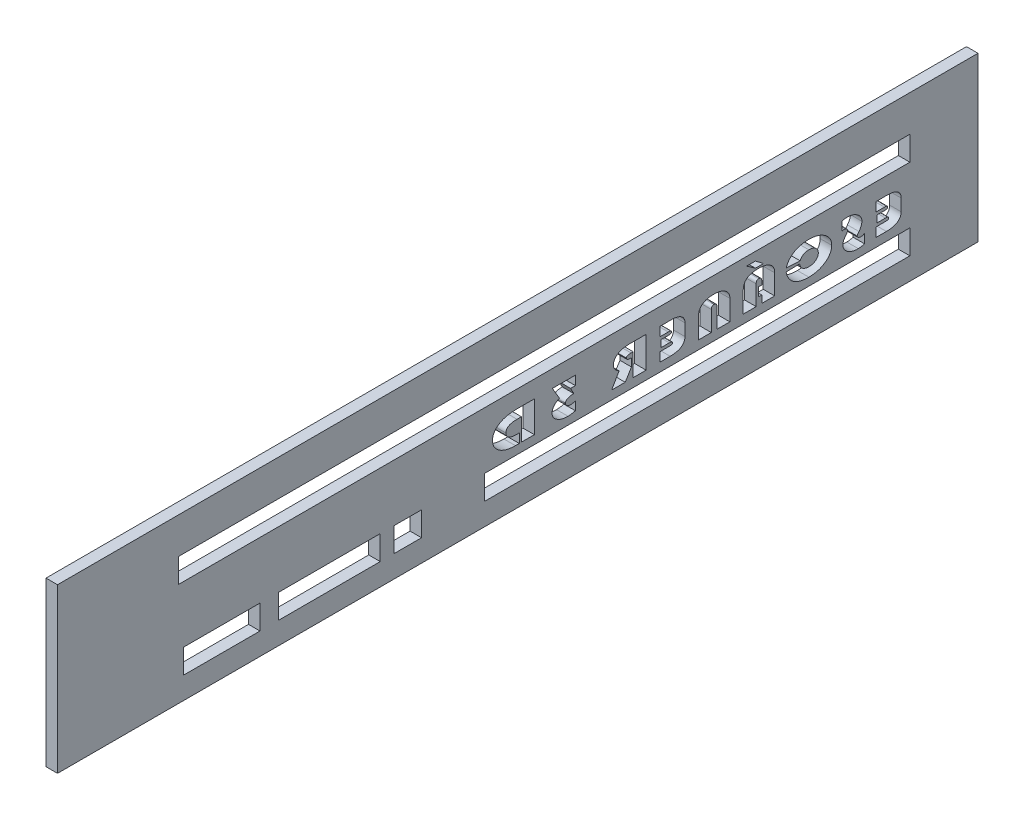
SolidWorks part; units mm, degrees
ref_plane "Alzado" through (0, 0, 0) normal (0, 0, 1) x (1, 0, 0)
ref_plane "Planta" through (0, 0, 0) normal (0, 1, 0) x (1, 0, 0)
ref_plane "Vista lateral" through (0, 0, 0) normal (1, 0, 0) x (0, 0, -1)
sketch "Croquis1" plane through (0, 0, 0) normal (1, 0, 0) x (0, 0, -1)
  line L0 (-140.2469, 35.5) -> (259.7531, 35.5)
  line L1 (-140.2469, 35.5) -> (-140.2469, -35.5)
  line L2 (-140.2469, -35.5) -> (259.7531, -35.5)
  line L3 (259.7531, 35.5) -> (259.7531, -35.5)
  dimension "D1" = 71
  dimension "D2" = 400
extrude "Saliente-Extruir1" add sketch "Croquis1" along normal blind 5
sketch "Croquis2" plane through (5, 0, 0) normal (1, 0, 0) x (0, 0, -1)
  line L0 (5.9231, -15.4) -> (17.9435, -15.4)
  line L1 (5.9231, -15.4) -> (5.9231, -25.9192)
  line L2 (5.9231, -25.9192) -> (17.9435, -25.9192)
  line L3 (17.9435, -15.4) -> (17.9435, -25.9192)
  line L4 (-140.2469, 35.5) -> (-140.2469, -35.5) construction
  line L5 (259.7531, 35.5) -> (-140.2469, 35.5) construction
  line L6 (-87.6715, 9.3149) -> (230.1429, 9.3149)
  line L15 (0, -15.4) -> (-44.1922, -15.4)
  line L16 (0, -15.4) -> (0, -25.9192)
  line L17 (0, -25.9192) -> (-44.1922, -25.9192)
  line L18 (-44.1922, -15.4) -> (-44.1922, -25.9192)
  line L19 (-52.2502, -15.4) -> (-85.4588, -15.4)
  line L20 (-52.2502, -15.4) -> (-52.2502, -25.9192)
  line L21 (-52.2502, -25.9192) -> (-85.4588, -25.9192)
  line L22 (-85.4588, -15.4) -> (-85.4588, -25.9192)
  line L23 (-87.6715, 9.3149) -> (-87.6715, 19.8341)
  line L24 (-87.6715, 19.8341) -> (230.1429, 19.8341)
  line L25 (230.1429, 9.3149) -> (230.1429, 19.8341)
  line L27 (230.1429, -15.4) -> (45.3818, -15.4)
  line L28 (230.1429, -15.4) -> (230.1429, -25.9192)
  line L29 (230.1429, -25.9192) -> (45.3818, -25.9192)
  line L30 (45.3818, -15.4) -> (45.3818, -25.9192)
  text T0 "ESCÁNER 3D" font "Bauhaus 93" height 13.5
  point P6 (5.9231, -20.6596)
  dimension "D1" = 12.0205
  dimension "D2" = 146.17
  dimension "D3" = 50.9
  dimension "D4" = 10.5192
  dimension "D5" = 10.5192
extrude "Cortar-Extruir1" cut sketch "Croquis2" against normal blind 10
